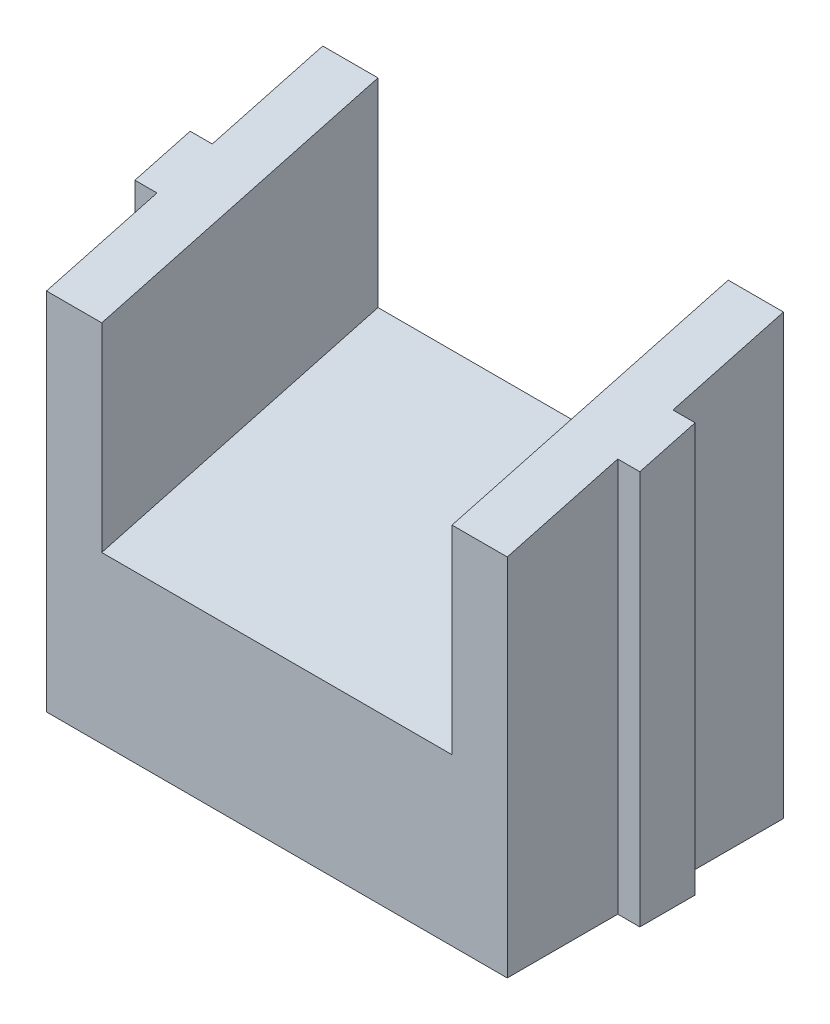
SolidWorks part; units mm, degrees
ref_plane "前基準面" through (0, 0, 0) normal (0, 0, 1) x (1, 0, 0)
ref_plane "上基準面" through (0, 0, 0) normal (0, 1, 0) x (1, 0, 0)
ref_plane "右基準面" through (0, 0, 0) normal (1, 0, 0) x (0, 0, -1)
sketch "草圖1" plane through (0, 0, 0) normal (0, 1, 0) x (1, 0, 0)
  line L1 (0, 0) -> (41.7, 0)
  line L2 (0, 0) -> (0, 25)
  line L3 (0, 25) -> (41.7, 25)
  line L4 (41.7, 0) -> (41.7, 25)
  line L5 (41.7, 15) -> (43.7, 15)
  line L6 (41.7, 15) -> (41.7, 10)
  line L7 (41.7, 10) -> (43.7, 10)
  line L8 (43.7, 15) -> (43.7, 10)
  line L9 (0, 15) -> (-2, 15)
  line L10 (0, 15) -> (0, 10)
  line L11 (0, 10) -> (-2, 10)
  line L12 (-2, 15) -> (-2, 10)
  dimension "D1" = 41.7
  dimension "D2" = 25
  dimension "D3" = 5
  dimension "D4" = 2
  dimension "D5" = 10
extrude "填料-伸長1" add sketch "草圖1" along normal blind 15 contours L9 L12 L11 L2 | L1 L4 L3 L2 | L8 L5 L4 L7
sketch "草圖2" plane through (41.7, 0, 0) normal (1, 0, 0) x (0, 0, -1)
  line L0 (0, 15) -> (25, 21.6987)
  line L1 (25, 21.6987) -> (25, 15)
  line L2 (25, 15) -> (25, 0) construction
  line L3 (0, 15) -> (10, 15) construction
  line L4 (0, 15) -> (25, 15)
  dimension "D1" = 15
extrude "填料-伸長2" add sketch "草圖2" against normal up to surface (41.7 mm away) up to face at (0, 7.5, -20)
sketch "草圖4" plane through (0, 13.9952, 3.75) normal (0, 0.9659, 0.2588) x (1, 0, 0)
  line L1 (0, 3.8823) -> (41.7, 3.8823)
  line L2 (0, 3.8823) -> (0, 29.7642)
  line L3 (0, 29.7642) -> (41.7, 29.7642)
  line L4 (41.7, 3.8823) -> (41.7, 29.7642)
  line L5 (5, 3.8823) -> (36.7, 3.8823)
  line L6 (5, 3.8823) -> (5, 29.7642)
  line L7 (5, 29.7642) -> (36.7, 29.7642)
  line L8 (36.7, 3.8823) -> (36.7, 29.7642)
  line M9 (41.7, 29.7642) -> (0, 29.7642)
  line M10 (0, 29.7642) -> (0, 3.8823)
  line M14 (0, 29.7642) -> (0, 3.8823)
  line M15 (0, 3.8823) -> (41.7, 3.8823)
  line M16 (41.7, 3.8823) -> (41.7, 29.7642)
  line M20 (41.7, 3.8823) -> (41.7, 29.7642)
  dimension "D1" = 5
  dimension "D2" = 5
extrude "填料-伸長4" add sketch "草圖4" along direction (0, -1, 0) on the side of the normal blind 18 contours L6 L3 L2 M15 M10 M14 | L8 L4 M15 M16 M20 M9
sketch "草圖3" plane through (0, 15, 0) normal (0, 1, 0) x (1, 0, 0)
  line L0 (41.7, 15) -> (41.7, 10) construction
  line L1 (41.7, 10) -> (43.7, 10) construction
  line L2 (43.7, 10) -> (43.7, 15) construction
  line L3 (43.7, 15) -> (41.7, 15) construction
  line L4 (-2, 10) -> (0, 10) construction
  line L5 (0, 10) -> (0, 15) construction
  line L6 (0, 15) -> (-2, 15) construction
  line L7 (-2, 15) -> (-2, 10) construction
  line L8 (41.7, 15) -> (41.7, 10)
  line L9 (41.7, 10) -> (43.7, 10)
  line L10 (43.7, 10) -> (43.7, 15)
  line L11 (43.7, 15) -> (41.7, 15)
  line L12 (-2, 10) -> (0, 10)
  line L13 (0, 10) -> (0, 15)
  line L14 (0, 15) -> (-2, 15)
  line L15 (-2, 15) -> (-2, 10)
extrude "填料-伸長3" add sketch "草圖3" along normal up to surface (20.6795 mm away)
